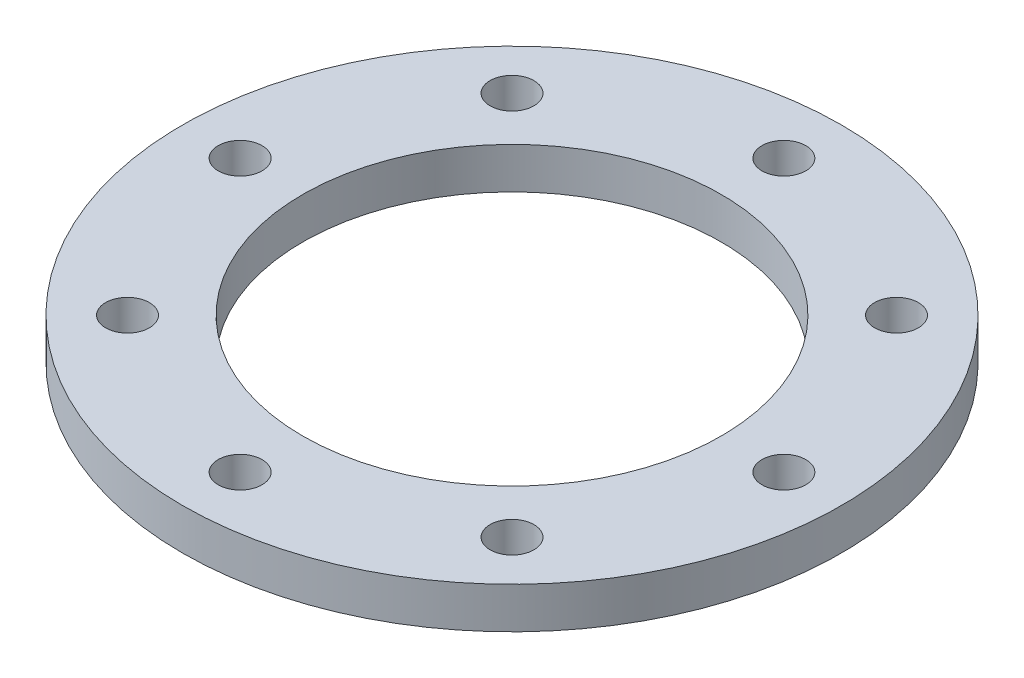
SolidWorks part; units mm, degrees
material "Plain Carbon Steel"
ref_plane "Front Plane" through (0, 0, 0) normal (0, 0, 1) x (1, 0, 0)
ref_plane "Top Plane" through (0, 0, 0) normal (0, 1, 0) x (1, 0, 0)
ref_plane "Right Plane" through (0, 0, 0) normal (1, 0, 0) x (0, 0, -1)
sketch "Sketch1" plane through (0, 0, 0) normal (0, 1, 0) x (1, 0, 0)
  circle A0 centre (0, 0) radius 50.8
  circle A1 centre (0, 0) radius 32.258
  dimension "D1" = 101.6
  dimension "D2" = 64.516
extrude "Boss-Extrude1" add sketch "Sketch1" along normal blind 6.35
hole_wizard "1/4 Clearance Hole1" positions "Sketch2" profile "Sketch3" hole size "1/4" standard "ANSI Inch" end condition through all
sketch "Sketch2" plane through (0, 6.35, 0) normal (0, 1, 0) x (1, 0, 0)
  point P0 (0, 41.91)
  dimension "D1" = 41.91
sketch "Sketch3" plane through (0, 6.35, -41.91) normal (1, 0, 0) x (0, 0, 1)
  line L0 (0, 0) -> (0, 6.35)
  line L1 (0, 6.35) -> (3.3782, 6.35)
  line L2 (3.3782, 6.35) -> (3.3782, 0)
  line L5 (3.3782, 0) -> (0, 0)
  line L11 (0, -6.35) -> (0, 107.95) construction
  dimension "Thru Hole Dia." = 6.7564
  dimension "Thru Hole Depth" = 6.35
pattern_circular "CirPattern1" count 8 over 360 about axis through (0, 0, 0) along (0, 1, 0) of "1/4 Clearance Hole1"
